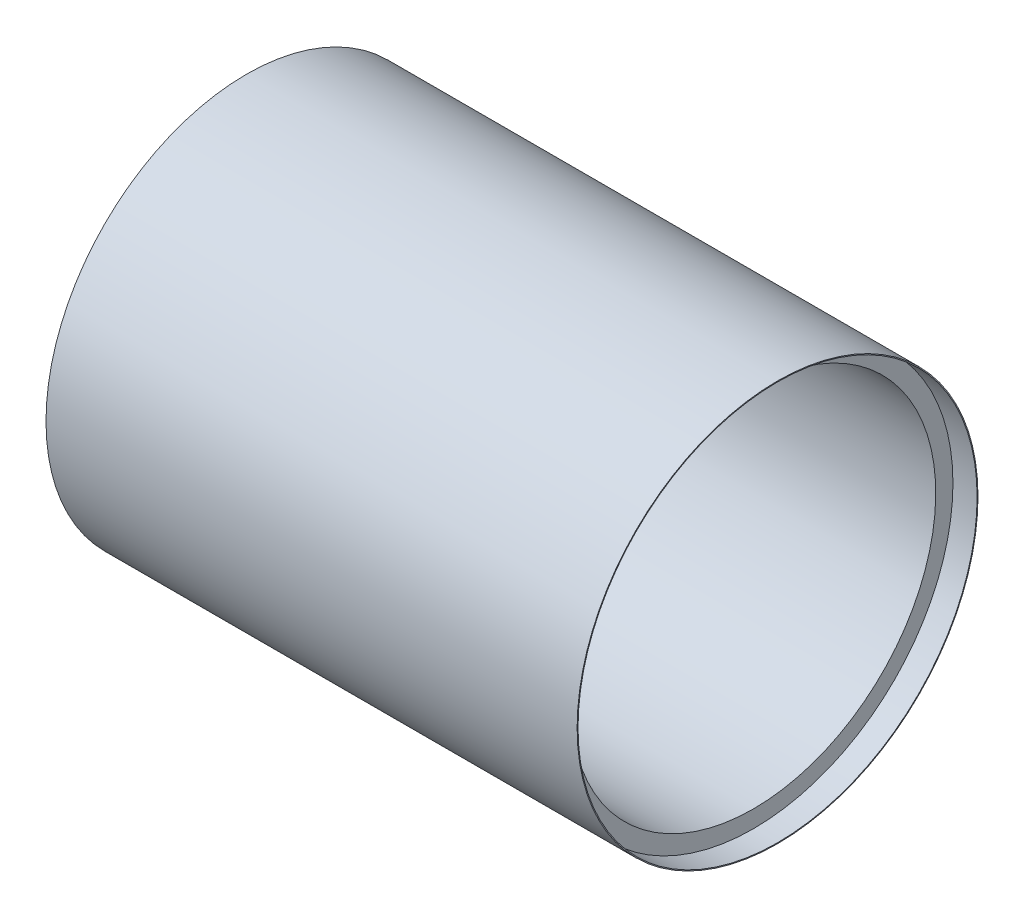
SolidWorks part; units mm, degrees
material "Thornel VCB-20 Carbon Cloth"
ref_plane "Front" through (0, 0, 0) normal (0, 0, 1) x (1, 0, 0)
ref_plane "Top" through (0, 0, 0) normal (0, 1, 0) x (1, 0, 0)
ref_plane "Right" through (0, 0, 0) normal (1, 0, 0) x (0, 0, -1)
sketch "Sketch1" plane through (0, 0, 0) normal (0, 0, 1) x (1, 0, 0)
  line L0 (39.1463, 83.9724) -> (49.3063, 83.9724)
  line L1 (49.3063, 83.9724) -> (49.3063, 76.7334)
  line L2 (49.3063, 76.7334) -> (252.5063, 76.7334)
  line L3 (252.5063, 76.7334) -> (252.5063, 83.9724)
  line L4 (252.5063, 83.9724) -> (262.6663, 83.9724)
  line L5 (262.6663, 83.9724) -> (262.6663, 84.3534)
  line L6 (262.6663, 84.3534) -> (39.1463, 84.3534)
  line L7 (39.1463, 84.3534) -> (39.1463, 83.9724)
  line L8 (0, 0) -> (134.0356, 0) construction
  dimension "D1" = 76.7334
  dimension "D2" = 0.381
  dimension "D3" = 10.16
  dimension "D4" = 10.16
  dimension "D5" = 203.2
  dimension "D6" = 84.3534
  dimension "D7" = 0.381
revolve "Revolve1" add sketch "Sketch1" angle 360 about L8
